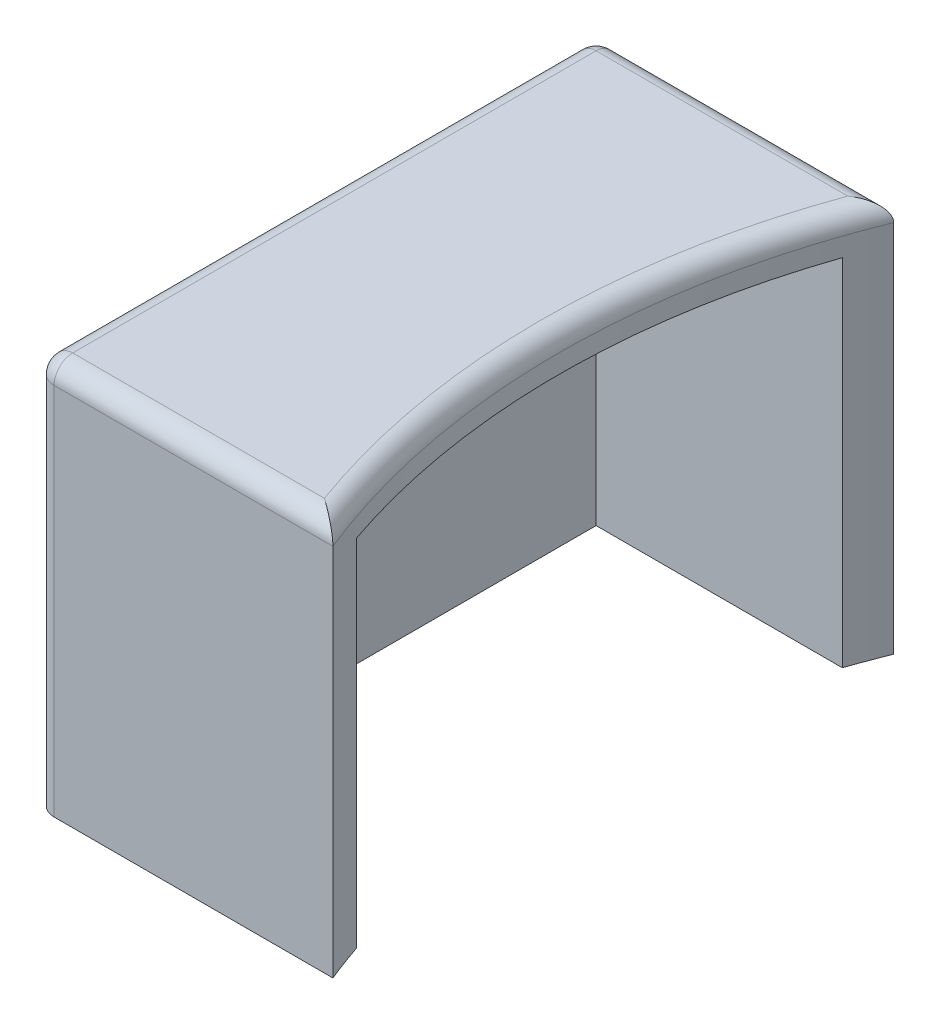
SolidWorks part; units mm, degrees
ref_plane "Front Plane" through (0, 0, 0) normal (0, 0, 1) x (1, 0, 0)
ref_plane "Top Plane" through (0, 0, 0) normal (0, 1, 0) x (1, 0, 0)
ref_plane "Right Plane" through (0, 0, 0) normal (1, 0, 0) x (0, 0, -1)
sketch "Sketch1" plane through (0, 0, 0) normal (0, 1, 0) x (1, 0, 0)
  line L0 (0, 0) -> (0, 30)
  line L2 (0, 0) -> (15.92, 0)
  line L3 (15.92, 30) -> (0, 30)
  line L5 (13, 15) -> (13.0009, 15) construction
  arc A0 (15.92, 30) -> (15.92, 0) centre (53, 15) ccw
  dimension "D1" = 15.92
  dimension "D2" = 30
  dimension "D3" = 15.92
extrude "Boss-Extrude1" add sketch "Sketch1" along normal blind 21
shell "Shell1" thickness 2
fillet "Fillet1" radius 1 6 edges at (13.0009, 21, -15) (0, 10.5, 0) (0, 10.5, -30) (0, 21, -15) (7.96, 21, 0) (7.96, 21, -30)
